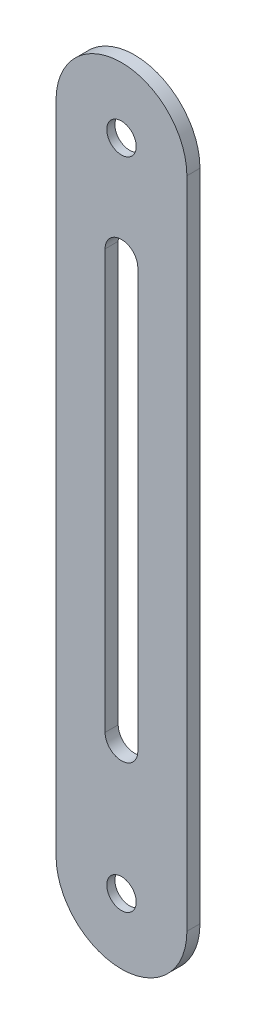
SolidWorks part; units mm, degrees
ref_plane "前视基准面" through (0, 0, 0) normal (0, 0, 1) x (1, 0, 0)
ref_plane "上视基准面" through (0, 0, 0) normal (0, 1, 0) x (1, 0, 0)
ref_plane "右视基准面" through (0, 0, 0) normal (1, 0, 0) x (0, 0, -1)
sketch "草图1" plane through (0, 0, 0) normal (0, 0, 1) x (1, 0, 0)
  line L0 (0, 0) -> (0, -200) construction
  line L3 (-20, 0) -> (-20, -200)
  line L5 (20, -200) -> (20, 0)
  circle A4 centre (0, 0) radius 8.75
  arc A5 (20, 0) -> (-20, 0) centre (0, 0) ccw
  arc A6 (-20, -200) -> (20, -200) centre (0, -200) ccw
  circle A7 centre (0, -200) radius 8.75
  dimension "D1" = 17.5
  dimension "D3" = 200
  dimension "D4" = 40
  dimension "D5" = 17.5
  dimension "D2" = 40
extrude "凸台-拉伸1" add sketch "草图1" along normal blind 4
sketch "草图3" plane through (0, 0, 4) normal (0, 0, 1) x (1, 0, 0)
  circle A0 centre (0, 0) radius 8.75 construction
  circle A1 centre (0, 0) radius 8.75
  circle A2 centre (0, 0) radius 4.5
  circle A3 centre (0, -200) radius 8.75 construction
  circle A4 centre (0, -200) radius 8.75
  circle A5 centre (0, -200) radius 4.5
  dimension "D1" = 9
  dimension "D2" = 9
extrude "凸台-拉伸2" add sketch "草图3" against normal blind 2.5
sketch "草图2" plane through (0, 0, 4) normal (0, 0, 1) x (1, 0, 0)
  line L13 (-5, 0) -> (-5, -200)
  line L14 (5, -200) -> (5, 0)
  line L15 (-5, -31.845) -> (-5, -159.845)
  line L16 (5, -159.845) -> (5, -31.845)
  arc A3 (-5, -31.845) -> (5, -31.845) centre (0, -31.845) cw
  arc A8 (-5, -200) -> (5, -200) centre (0, -200) ccw
  arc A10 (-5, -159.845) -> (5, -159.845) centre (0, -159.845) ccw
  dimension "D1" = 15
extrude "切除-拉伸2" cut sketch "草图2" against normal through all
